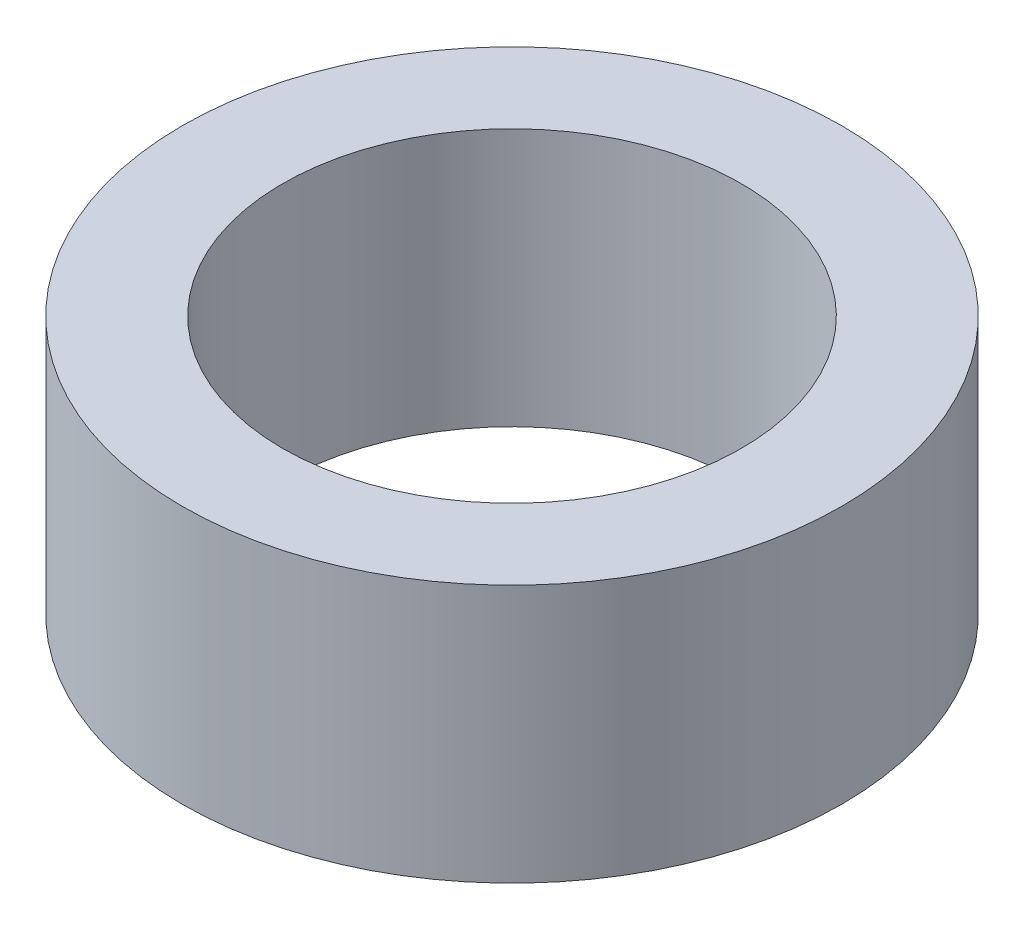
SolidWorks part; units mm, degrees
ref_plane "前视基准面" through (0, 0, 0) normal (0, 0, 1) x (1, 0, 0)
ref_plane "上视基准面" through (0, 0, 0) normal (0, 1, 0) x (1, 0, 0)
ref_plane "右视基准面" through (0, 0, 0) normal (1, 0, 0) x (0, 0, -1)
sketch "草图1" plane through (0, 0, 0) normal (0, 1, 0) x (1, 0, 0)
  circle A0 centre (0, 0) radius 1.6
  circle A1 centre (0, 0) radius 2.3
  dimension "D1" = 3.2
  dimension "D2" = 0.7
extrude "凸台-拉伸1" add sketch "草图1" along normal blind 1.8
